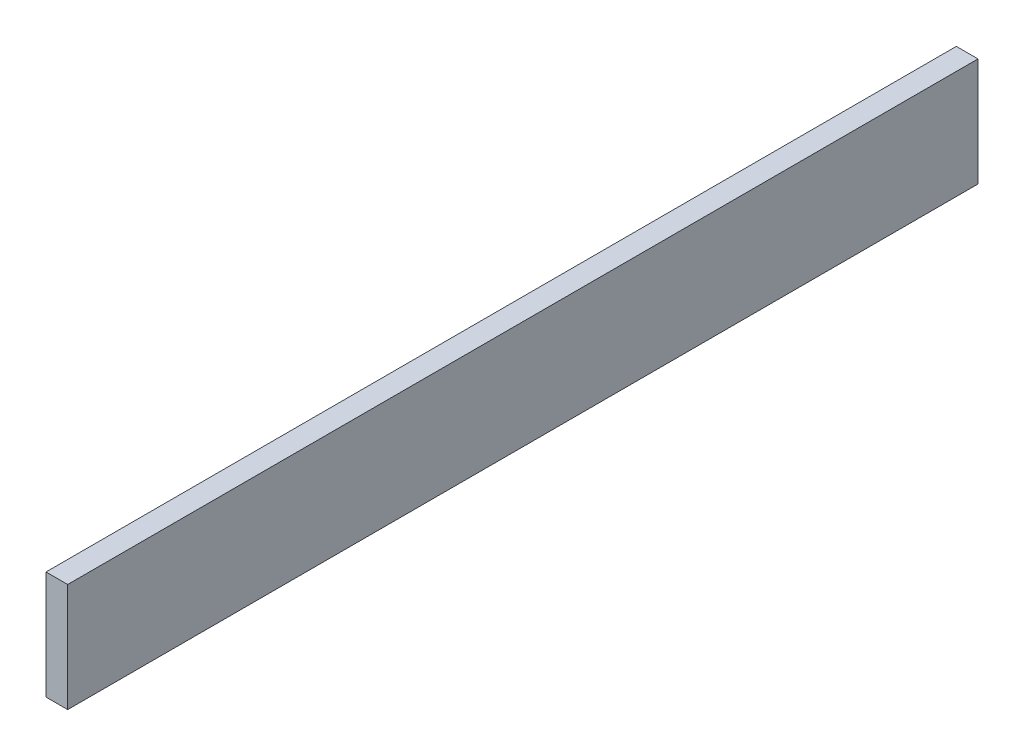
SolidWorks part; units mm, degrees
material "ASTM A36 Steel"
ref_plane "Front Plane" through (0, 0, 0) normal (0, 0, 1) x (1, 0, 0)
ref_plane "Top Plane" through (0, 0, 0) normal (0, 1, 0) x (1, 0, 0)
ref_plane "Right Plane" through (0, 0, 0) normal (1, 0, 0) x (0, 0, -1)
sketch "Sketch1" plane through (0, 0, 0) normal (1, 0, 0) x (0, 0, -1)
  line L1 (-63, -7.5) -> (63, -7.5)
  line L2 (-63, -7.5) -> (-63, 7.5)
  line L3 (-63, 7.5) -> (63, 7.5)
  line L4 (63, -7.5) -> (63, 7.5)
  line L5 (-63, -7.5) -> (63, 7.5) construction
  line L6 (-63, 7.5) -> (63, -7.5) construction
  point P0 (0, 0)
  dimension "D1" = 126
  dimension "D2" = 15
extrude "Boss-Extrude1" add sketch "Sketch1" along normal blind 3
